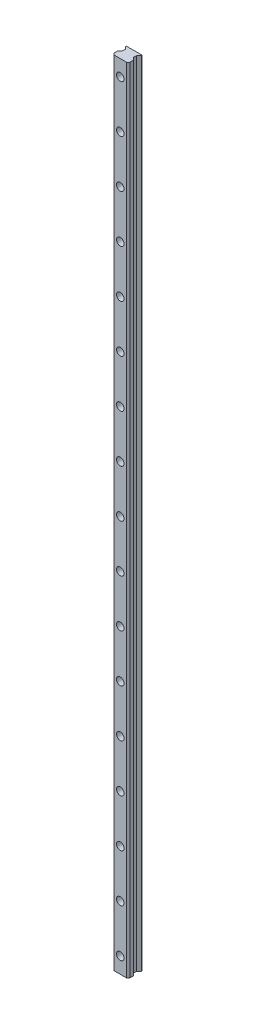
SolidWorks part; units mm, degrees
material "延性铁"
ref_plane "前视基准面" through (0, 0, 0) normal (0, 0, 1) x (1, 0, 0)
ref_plane "上视基准面" through (0, 0, 0) normal (0, 1, 0) x (1, 0, 0)
ref_plane "右视基准面" through (0, 0, 0) normal (1, 0, 0) x (0, 0, -1)
other "Configuration Table"
sketch "草图1" plane through (0, 0, 0) normal (0, 1, 0) x (1, 0, 0)
  line L1 (-10, 8.75) -> (10, 8.75)
  line L2 (-10, 8.75) -> (-10, -8.75)
  line L3 (-10, -8.75) -> (10, -8.75)
  line L4 (10, 8.75) -> (10, -8.75)
  point P4 (-10, 0)
  point P6 (0, 8.75)
  dimension "D1" = 20
  dimension "D2" = 17.5
extrude "凸台-拉伸1" add sketch "草图1" along normal blind 1000
sketch "草图2" plane through (0, 0, 0) normal (0, -1, 0) x (1, 0, 0)
  line L2 (-8, 8.75) -> (-10, 6.75)
  line L3 (10, 6.75) -> (8, 8.75)
  line L4 (0, 0) -> (0, 2.9892) construction
  line L5 (10, 2.25) -> (7, -0.75)
  line L6 (-10, 8.75) -> (-10, -8.75)
  line L7 (-10, -8.75) -> (10, -8.75)
  line L12 (10, -8.75) -> (10, 8.75)
  line L13 (10, 8.75) -> (-10, 8.75)
  line L17 (10, -7.75) -> (10, 2.25)
  line L19 (7, -0.75) -> (7, -4.75)
  line L20 (7, -4.75) -> (10, -7.75)
  line L21 (10, 8.75) -> (10, -8.75) construction
  line L22 (8, 8.75) -> (10, 8.75)
  line L23 (10, 8.75) -> (10, 6.75)
  line L24 (-10, 8.75) -> (-10, 6.75)
  line L25 (-10, 8.75) -> (-8, 8.75)
  line L26 (-7, -4.75) -> (-10, -7.75)
  line L27 (-7, -0.75) -> (-7, -4.75)
  line L28 (-10, -7.75) -> (-10, 2.25)
  line L29 (-10, 2.25) -> (-7, -0.75)
  dimension "D2" = 45
  dimension "D3" = 45
  dimension "D6" = 1
  dimension "D4" = 4
  dimension "D5" = 10
  dimension "D1" = 0
extrude "切除-拉伸1" cut sketch "草图2" against normal through all
sketch "草图3" plane through (0, 0, 8.75) normal (0, 0, 1) x (1, 0, 0)
  line L0 (-8, 1000) -> (8, 1000) construction
  circle A0 centre (0, 980) radius 3
  circle A1 centre (0, 920) radius 3
  circle A2 centre (0, 860) radius 3
  circle A3 centre (0, 800) radius 3
  circle A4 centre (0, 740) radius 3
  circle A5 centre (0, 680) radius 3
  circle A6 centre (0, 620) radius 3
  circle A7 centre (0, 560) radius 3
  circle A8 centre (0, 500) radius 3
  circle A9 centre (0, 440) radius 3
  circle A10 centre (0, 380) radius 3
  circle A11 centre (0, 320) radius 3
  circle A12 centre (0, 260) radius 3
  circle A13 centre (0, 200) radius 3
  circle A14 centre (0, 140) radius 3
  circle A15 centre (0, 80) radius 3
  circle A16 centre (0, 20) radius 3
  point P4 (0, 1000)
  dimension "D1" = 6
  dimension "D2" = 20
  dimension "D3" = 17
extrude "切除-拉伸2" cut sketch "草图3" against normal through all
sketch "草图4" plane through (0, 0, 8.75) normal (0, 0, 1) x (1, 0, 0)
  circle A0 centre (0, 980) radius 3 construction
  circle A1 centre (0, 980) radius 3 construction
  circle A2 centre (0, 980) radius 4.75
  circle A3 centre (0, 920) radius 4.75
  circle A4 centre (0, 860) radius 4.75
  circle A5 centre (0, 800) radius 4.75
  circle A6 centre (0, 740) radius 4.75
  circle A7 centre (0, 680) radius 4.75
  circle A8 centre (0, 620) radius 4.75
  circle A9 centre (0, 560) radius 4.75
  circle A10 centre (0, 500) radius 4.75
  circle A11 centre (0, 440) radius 4.75
  circle A12 centre (0, 380) radius 4.75
  circle A13 centre (0, 320) radius 4.75
  circle A14 centre (0, 260) radius 4.75
  circle A15 centre (0, 200) radius 4.75
  circle A16 centre (0, 140) radius 4.75
  circle A17 centre (0, 80) radius 4.75
  circle A18 centre (0, 20) radius 4.75
  dimension "D1" = 9.5
  dimension "D2" = 17
extrude "切除-拉伸3" cut sketch "草图4" against normal blind 10
